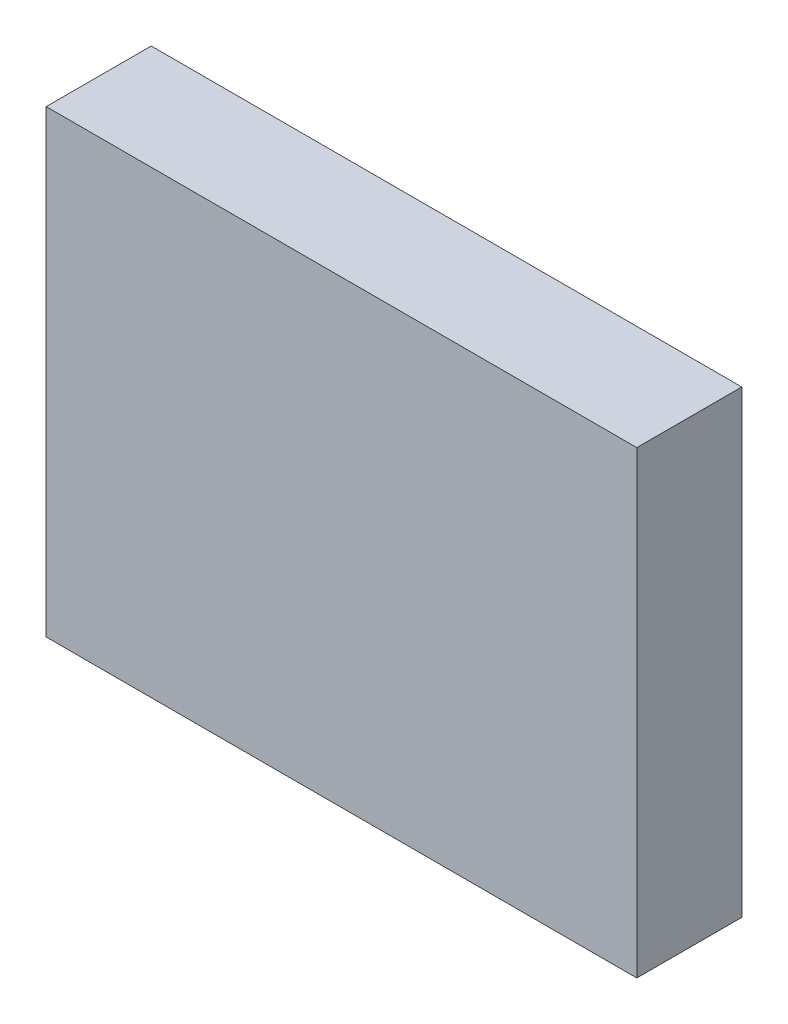
SolidWorks part; units mm, degrees
ref_plane "前基準面" through (0, 0, 0) normal (0, 0, 1) x (1, 0, 0)
ref_plane "上基準面" through (0, 0, 0) normal (0, 1, 0) x (1, 0, 0)
ref_plane "右基準面" through (0, 0, 0) normal (1, 0, 0) x (0, 0, -1)
sketch "草圖1" plane through (0, 0, 0) normal (0, 0, 1) x (1, 0, 0)
  line L1 (-12.9064, 28.838) -> (77.0936, 28.838)
  line L2 (-12.9064, 28.838) -> (-12.9064, -41.162)
  line L3 (-12.9064, -41.162) -> (77.0936, -41.162)
  line L4 (77.0936, 28.838) -> (77.0936, -41.162)
  dimension "D1" = 90
  dimension "D2" = 70
extrude "填料-伸長1" add sketch "草圖1" along normal blind 16
